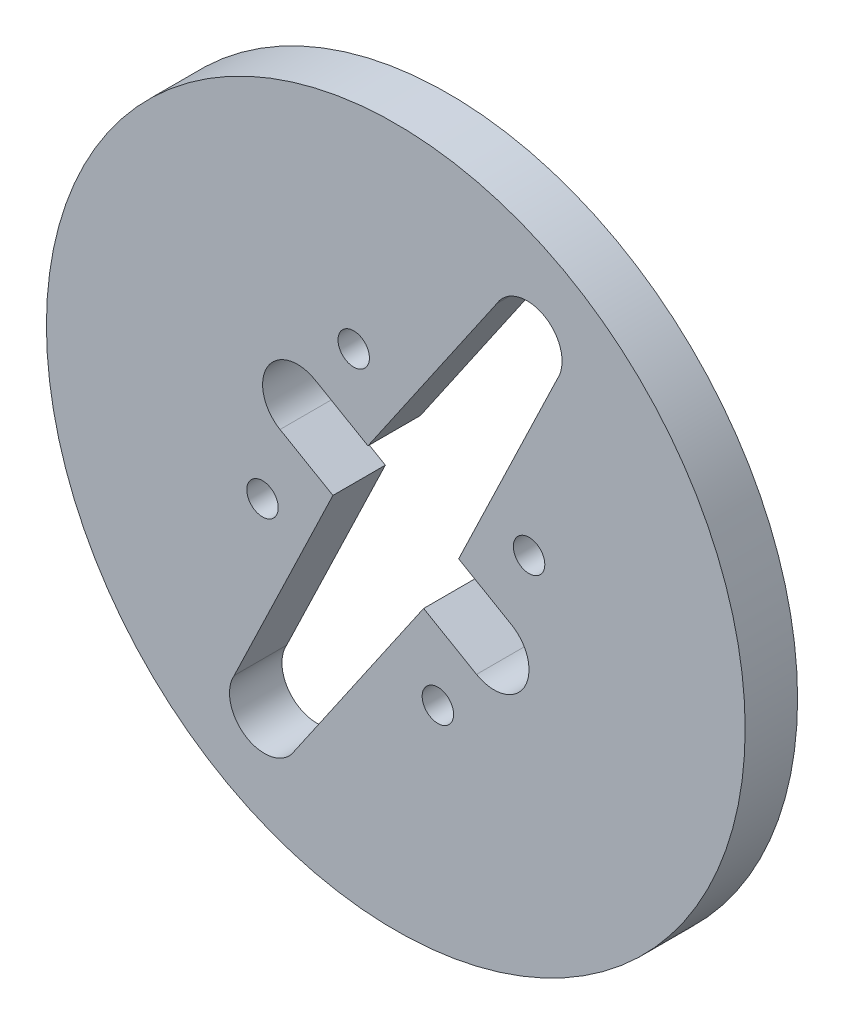
SolidWorks part; units mm, degrees
ref_plane "Front Plane" through (0, 0, 0) normal (0, 0, 1) x (1, 0, 0)
ref_plane "Top Plane" through (0, 0, 0) normal (0, 1, 0) x (1, 0, 0)
ref_plane "Right Plane" through (0, 0, 0) normal (1, 0, 0) x (0, 0, -1)
sketch "Sketch1" plane through (0, 0, 0) normal (0, 0, 1) x (1, 0, 0)
  line L0 (-5.6246, 3.258) -> (5.6246, -3.258) construction
  line L1 (-4.6221, 4.9886) -> (6.627, -1.5273)
  line L2 (-6.627, 1.5273) -> (4.6221, -4.9886)
  line L3 (3.5984, 0.227) -> (-1.5935, 3.2343)
  line L4 (1.0025, 1.7306) -> (7.5184, 12.9797) construction
  line L5 (5.7878, 13.9822) -> (9.249, 11.9773)
  line L6 (-1.5935, 3.2343) -> (5.7878, 13.9822)
  line L7 (3.5984, 0.227) -> (9.249, 11.9773)
  line L8 (-5.6246, 3.258) -> (5.6246, -3.258)
  line L9 (1.5935, -3.2343) -> (-3.5984, -0.227)
  line L10 (-3.5984, -0.227) -> (-9.249, -11.9773)
  line L11 (-9.249, -11.9773) -> (-5.7878, -13.9822)
  line L12 (1.5935, -3.2343) -> (-5.7878, -13.9822)
  circle A0 centre (0, 0) radius 20
  arc A1 (-4.6221, 4.9886) -> (-6.627, 1.5273) centre (-5.6246, 3.258) ccw
  arc A2 (4.6221, -4.9886) -> (6.627, -1.5273) centre (5.6246, -3.258) ccw
  circle A3 centre (7.5184, 12.9797) radius 2
  circle A4 centre (-7.5184, -12.9797) radius 2
  point P5 (0, 0)
  point P14 (1.0025, 1.7306)
  point P18 (7.5184, 12.9797)
  point P22 (0, 0)
  dimension "D1" = 13
  dimension "D2" = 6
  dimension "D3" = 13
  dimension "D4" = 4
extrude "Boss-Extrude1" add sketch "Sketch1" along normal blind 3 contours A0 L12 A4 L10 L2 A1 L1 L6 A3 L7 A2
sketch "Sketch2" plane through (0, 0, 0) normal (0, 0, -1) x (-1, 0, 0)
  line L0 (0, 0) -> (-2.409, -7.6287) construction
  circle A0 centre (-2.409, -7.6287) radius 0.9
  circle A1 centre (-7.6287, 2.409) radius 0.9
  circle A2 centre (2.409, 7.6287) radius 0.9
  circle A3 centre (7.6287, -2.409) radius 0.9
  point P13 (0, 0)
  dimension "D2" = 4
  dimension "D1" = 8
extrude "Cut-Extrude1" cut sketch "Sketch2" against normal blind 3
